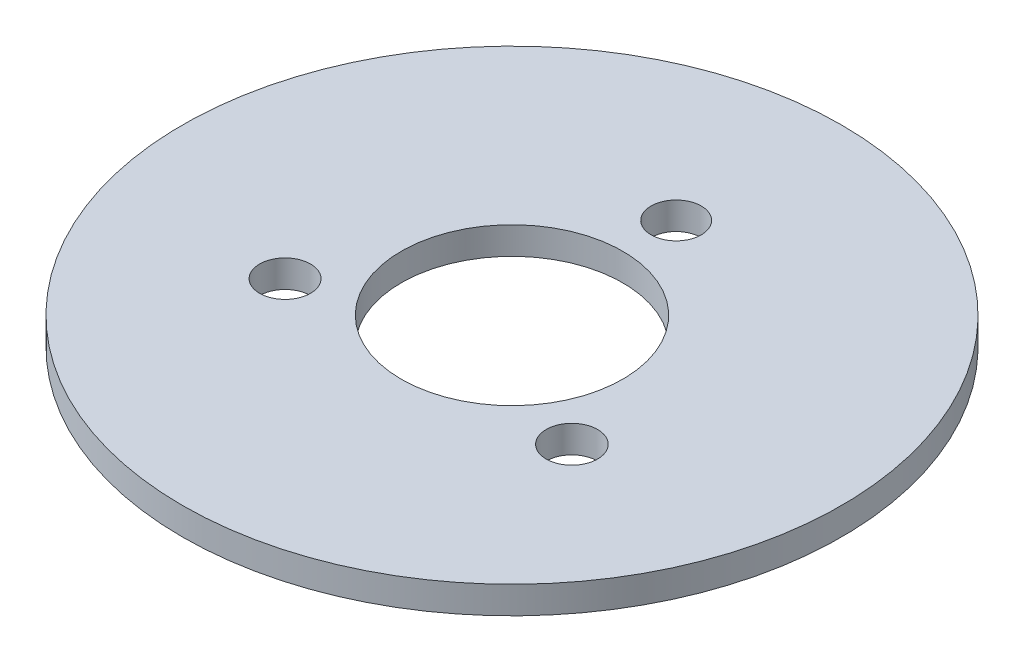
SolidWorks part; units mm, degrees
ref_plane "Front Plane" through (0, 0, 0) normal (0, 0, 1) x (1, 0, 0)
ref_plane "Top Plane" through (0, 0, 0) normal (0, 1, 0) x (1, 0, 0)
ref_plane "Right Plane" through (0, 0, 0) normal (1, 0, 0) x (0, 0, -1)
sketch "Sketch1" plane through (0, 0, 0) normal (0, 1, 0) x (1, 0, 0)
  line L0 (0, 0) -> (0, 19.05) construction
  line L1 (0, 0) -> (11.1378, -6.4304) construction
  line L2 (11.1378, -6.4304) -> (16.4445, -9.4942) construction
  line L3 (0, 0) -> (-11.2031, -6.3158) construction
  line L4 (-11.2031, -6.3158) -> (-16.8412, -9.4942) construction
  circle A0 centre (0, 0) radius 38.2439
  circle A1 centre (0, 0) radius 12.8604
  arc A2 (0.1319, 12.8601) -> (11.1378, -6.4304) centre (0, 0) cw
  arc A3 (0.1319, 12.8601) -> (-11.2031, -6.3158) centre (0, 0) cw
  circle A4 centre (-16.8412, -9.4942) radius 2.9529
  circle A5 centre (16.4445, -9.4942) radius 2.9796
  circle A6 centre (0, 19.05) radius 2.9091
extrude "Boss-Extrude1" add sketch "Sketch1" along normal blind 3.175
